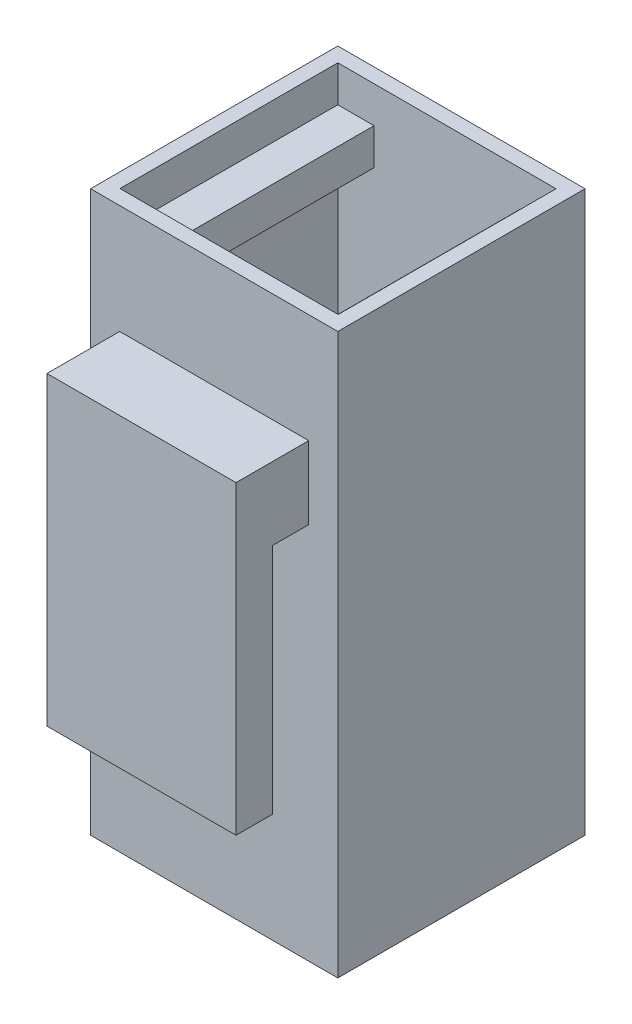
SolidWorks part; units mm, degrees
ref_plane "Front Plane" through (0, 0, 0) normal (0, 0, 1) x (1, 0, 0)
ref_plane "Top Plane" through (0, 0, 0) normal (0, 1, 0) x (1, 0, 0)
ref_plane "Right Plane" through (0, 0, 0) normal (1, 0, 0) x (0, 0, -1)
sketch "Sketch1" plane through (0, 0, 0) normal (0, 1, 0) x (1, 0, 0)
  line L0 (0, 0) -> (30, 0)
  line L1 (0, 0) -> (0, -30)
  line L2 (30, 0) -> (30, -30)
  line L3 (0, -30) -> (30, -30)
  line L4 (-2, 2) -> (32, 2)
  line L5 (-2, 2) -> (-2, -32)
  line L6 (32, 2) -> (32, -32)
  line L7 (-2, -32) -> (32, -32)
  dimension "D1" = 30
  dimension "D2" = 30
  dimension "D3" = 2
  dimension "D4" = 2
  dimension "D5" = 2
  dimension "D6" = 2
extrude "Boss-Extrude1" add sketch "Sketch1" along normal blind 75
sketch "Sketch3" plane through (0, 75, 0) normal (0, 1, 0) x (1, 0, 0)
  line L0 (0, 0) -> (4.9817, 0)
  line L1 (30, 0) -> (0, 0) construction
  line L2 (4.9817, 0) -> (4.9817, -25)
  line L3 (4.9817, -25) -> (24.9817, -25)
  line L4 (24.9817, -25) -> (24.9817, 0)
  line L5 (24.9817, 0) -> (30, 0)
  line L6 (30, 0) -> (30, -30)
  line L7 (30, -30) -> (0, -30)
  line L8 (0, -30) -> (0, 0)
  dimension "D1" = 25
  dimension "D2" = 20
extrude "Boss-Extrude2" add sketch "Sketch3" against normal blind 10
sketch "Sketch4" plane through (0, 75, 0) normal (0, 1, 0) x (1, 0, 0)
  line L0 (24.9817, 0) -> (30.0079, 0)
  line L1 (30.0079, 0) -> (30.0079, -29.951)
  line L2 (30.0079, -29.951) -> (0, -29.951)
  line L3 (0, -29.951) -> (0, 0)
  line L4 (0, 0) -> (4.9817, 0)
  line L5 (4.9817, 0) -> (4.9817, -25)
  line L6 (4.9817, -25) -> (24.9817, -25)
  line L7 (24.9817, -25) -> (24.9817, 0)
extrude "Cut-Extrude1" cut sketch "Sketch4" against normal blind 5
sketch "Sketch7" plane through (0, 0, 0) normal (0, -1, 0) x (1, 0, 0)
  line L0 (-2, 32) -> (-2, -2)
  line L1 (-2, 32) -> (32, 32)
  line L2 (-2, -2) -> (32, -2)
  line L3 (32, 32) -> (32, -2)
extrude "Boss-Extrude3" add sketch "Sketch7" along normal blind 2
sketch "Sketch8" plane through (0, 0, 32) normal (0, 0, 1) x (1, 0, 0)
  line L0 (2, 60) -> (28, 60)
  line L1 (2, 60) -> (2, 18)
  line L2 (28, 60) -> (28, 18)
  line L3 (2, 18) -> (28, 18)
  line L4 (-2, 75) -> (-2, -2) construction
  line L5 (32, 75) -> (32, -2) construction
  line L6 (32, -2) -> (-2, -2) construction
  line L7 (-2, 75) -> (32, 75) construction
  dimension "D1" = 4
  dimension "D2" = 4
  dimension "D3" = 20
  dimension "D4" = 15
extrude "Boss-Extrude4" add sketch "Sketch8" along normal blind 10
sketch "Sketch9" plane through (2, 0, 0) normal (-1, 0, 0) x (0, 0, 1)
  line L0 (32, 50) -> (37, 50)
  line L1 (32, 50) -> (32, 17.9821)
  line L2 (37, 50) -> (37, 17.9821)
  line L3 (32, 17.9821) -> (37, 17.9821)
  line L4 (32, 60) -> (32, 18) construction
  line L5 (42, 60) -> (32, 60) construction
  dimension "D1" = 10
  dimension "D2" = 5
extrude "Cut-Extrude2" cut sketch "Sketch9" against normal blind 28
